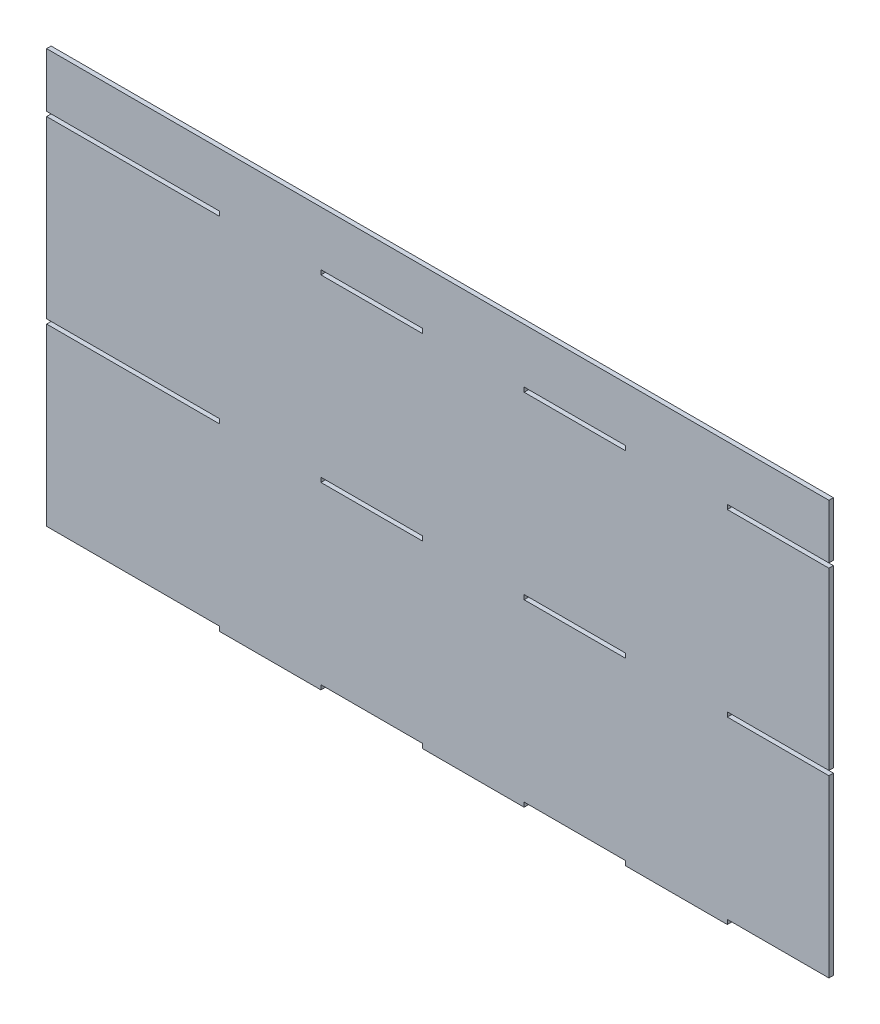
SolidWorks part; units mm, degrees
material "Acrylic (Medium-high impact)"
ref_plane "Front Plane" through (0, 0, 0) normal (0, 0, 1) x (1, 0, 0)
ref_plane "Top Plane" through (0, 0, 0) normal (0, 1, 0) x (1, 0, 0)
ref_plane "Right Plane" through (0, 0, 0) normal (1, 0, 0) x (0, 0, -1)
sketch "Sketch1" plane through (0, 0, 0) normal (0, 0, 1) x (1, 0, 0)
  line L0 (50.8998, 255.8625) -> (-70.5288, 255.8625) construction
  line L1 (50.8998, -0.0125) -> (122.3283, -0.0125)
  line L6 (479.4712, 3.1625) -> (408.0426, 3.1625) construction
  line L7 (408.0426, -0.0125) -> (408.0426, 3.1625) construction
  line L8 (336.614, -0.0125) -> (336.614, 3.1625) construction
  line L9 (336.614, 3.1625) -> (265.1855, 3.1625) construction
  line L10 (265.1855, -0.0125) -> (265.1855, 3.1625) construction
  line L11 (193.7569, -0.0125) -> (193.7569, 3.1625) construction
  line L12 (193.7569, 3.1625) -> (122.3283, 3.1625) construction
  line L13 (122.3283, -0.0125) -> (122.3283, 3.1625) construction
  line L14 (50.8998, -0.0125) -> (50.8998, 3.1625) construction
  line L15 (50.8998, 255.8625) -> (-70.5288, 255.8625)
  line L16 (479.4712, 3.1625) -> (408.0426, 3.1625)
  line L17 (408.0426, -0.0125) -> (408.0426, 3.1625)
  line L18 (336.614, -0.0125) -> (336.614, 3.1625)
  line L19 (336.614, 3.1625) -> (265.1855, 3.1625)
  line L20 (265.1855, -0.0125) -> (265.1855, 3.1625)
  line L21 (193.7569, -0.0125) -> (193.7569, 3.1625)
  line L22 (193.7569, 3.1625) -> (122.3283, 3.1625)
  line L23 (122.3283, -0.0125) -> (122.3283, 3.1625)
  line L24 (50.8998, -0.0125) -> (50.8998, 3.1625)
  line L26 (193.7569, -0.0125) -> (265.1855, -0.0125)
  line L27 (336.614, -0.0125) -> (408.0426, -0.0125)
  line L33 (479.4712, 294.0375) -> (479.4712, 255.8625)
  line L34 (50.8998, 252.6875) -> (-70.5288, 252.6875) construction
  line L35 (50.8998, 252.6875) -> (-70.5288, 252.6875)
  line L38 (50.8998, 126.3375) -> (-70.5288, 126.3375) construction
  line L39 (50.8998, 126.3375) -> (-70.5288, 126.3375)
  line L40 (50.8998, 129.5125) -> (-70.5288, 129.5125) construction
  line L41 (50.8998, 129.5125) -> (-70.5288, 129.5125)
  line L58 (50.8998, 3.1625) -> (-70.5288, 3.1625) construction
  line L61 (50.8998, 3.1625) -> (-70.5288, 3.1625)
  line L62 (-70.5288, 255.8625) -> (-70.5288, 294.0375)
  line L63 (-70.5288, 294.0375) -> (-20.5288, 294.0375)
  line L64 (-70.5288, 252.6875) -> (-70.5288, 129.5125)
  line L65 (-70.5288, 126.3375) -> (-70.5288, 3.1625)
  line L82 (479.4712, 294.0375) -> (166.4712, 294.0375) construction
  line L83 (479.4712, 294.0375) -> (166.4712, 294.0375)
  line L84 (166.4712, 294.0375) -> (-20.5288, 294.0375)
  line L85 (479.4712, 126.3375) -> (408.0426, 126.3375) construction
  line L86 (408.0426, 126.3375) -> (408.0426, 129.5125) construction
  line L87 (479.4712, 129.5125) -> (408.0426, 129.5125) construction
  line L88 (408.0426, 252.6875) -> (408.0426, 255.8625) construction
  line L89 (479.4712, 252.6875) -> (408.0426, 252.6875) construction
  line L90 (479.4712, 255.8625) -> (408.0426, 255.8625) construction
  line L91 (336.614, 126.3375) -> (336.614, 129.5125) construction
  line L92 (336.614, 126.3375) -> (265.1855, 126.3375) construction
  line L93 (265.1855, 126.3375) -> (265.1855, 129.5125) construction
  line L94 (336.614, 129.5125) -> (265.1855, 129.5125) construction
  line L95 (336.614, 252.6875) -> (336.614, 255.8625) construction
  line L96 (336.614, 252.6875) -> (265.1855, 252.6875) construction
  line L97 (265.1855, 252.6875) -> (265.1855, 255.8625) construction
  line L98 (336.614, 255.8625) -> (265.1855, 255.8625) construction
  line L99 (193.7569, 126.3375) -> (193.7569, 129.5125) construction
  line L100 (193.7569, 126.3375) -> (122.3283, 126.3375) construction
  line L101 (193.7569, 129.5125) -> (122.3283, 129.5125) construction
  line L102 (122.3283, 126.3375) -> (122.3283, 129.5125) construction
  line L103 (193.7569, 252.6875) -> (193.7569, 255.8625) construction
  line L104 (193.7569, 252.6875) -> (122.3283, 252.6875) construction
  line L105 (122.3283, 252.6875) -> (122.3283, 255.8625) construction
  line L106 (193.7569, 255.8625) -> (122.3283, 255.8625) construction
  line L107 (50.8998, 126.3375) -> (50.8998, 129.5125) construction
  line L110 (50.8998, 252.6875) -> (50.8998, 255.8625) construction
  line L113 (479.4712, 126.3375) -> (408.0426, 126.3375)
  line L114 (408.0426, 126.3375) -> (408.0426, 129.5125)
  line L115 (479.4712, 129.5125) -> (408.0426, 129.5125)
  line L116 (408.0426, 252.6875) -> (408.0426, 255.8625)
  line L117 (479.4712, 252.6875) -> (408.0426, 252.6875)
  line L118 (479.4712, 255.8625) -> (408.0426, 255.8625)
  line L119 (336.614, 126.3375) -> (336.614, 129.5125)
  line L120 (336.614, 126.3375) -> (265.1855, 126.3375)
  line L121 (265.1855, 126.3375) -> (265.1855, 129.5125)
  line L122 (336.614, 129.5125) -> (265.1855, 129.5125)
  line L123 (336.614, 252.6875) -> (336.614, 255.8625)
  line L124 (336.614, 252.6875) -> (265.1855, 252.6875)
  line L125 (265.1855, 252.6875) -> (265.1855, 255.8625)
  line L126 (336.614, 255.8625) -> (265.1855, 255.8625)
  line L127 (193.7569, 126.3375) -> (193.7569, 129.5125)
  line L128 (193.7569, 126.3375) -> (122.3283, 126.3375)
  line L129 (193.7569, 129.5125) -> (122.3283, 129.5125)
  line L130 (122.3283, 126.3375) -> (122.3283, 129.5125)
  line L131 (193.7569, 252.6875) -> (193.7569, 255.8625)
  line L132 (193.7569, 252.6875) -> (122.3283, 252.6875)
  line L133 (122.3283, 252.6875) -> (122.3283, 255.8625)
  line L134 (193.7569, 255.8625) -> (122.3283, 255.8625)
  line L135 (50.8998, 126.3375) -> (50.8998, 129.5125)
  line L138 (50.8998, 252.6875) -> (50.8998, 255.8625)
  line L141 (479.4712, 252.6875) -> (479.4712, 129.5125)
  line L142 (479.4712, 126.3375) -> (479.4712, 3.1625)
extrude "Boss-Extrude1" add sketch "Sketch1" along normal blind 3.175
